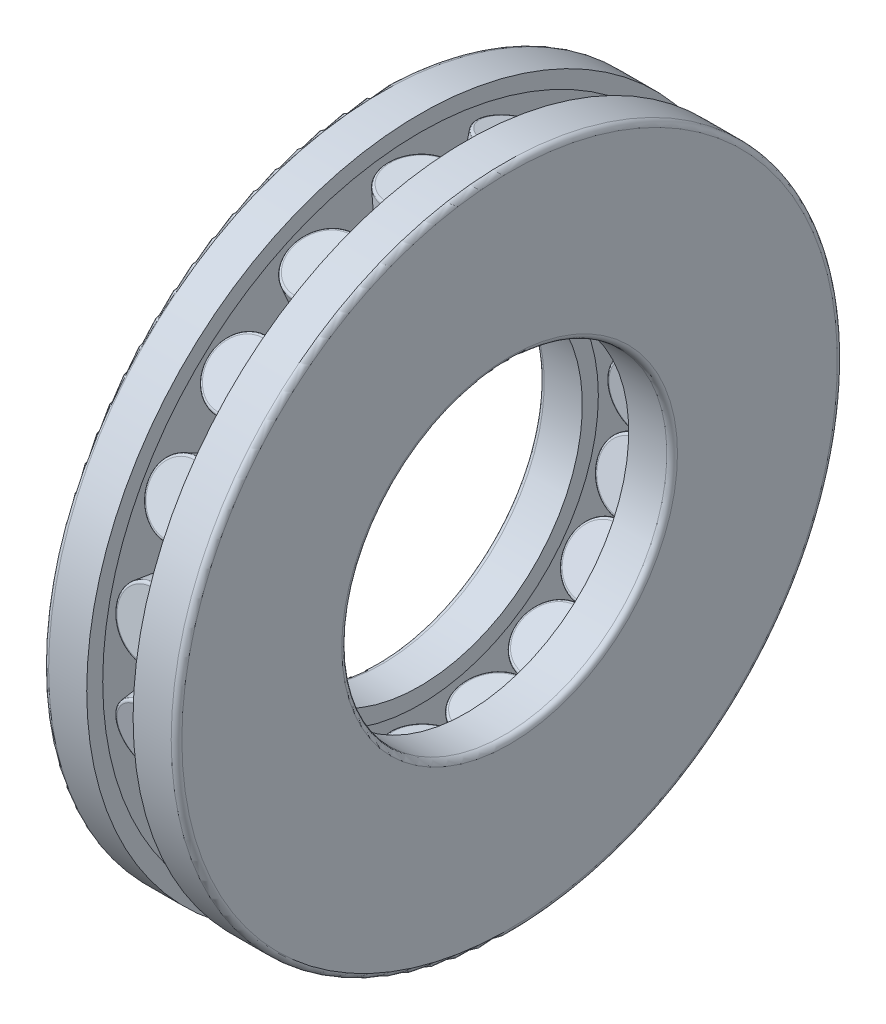
SolidWorks part; units mm, degrees
ref_plane "Front Plane" through (0, 0, 0) normal (0, 0, 1) x (1, 0, 0)
ref_plane "Top Plane" through (0, 0, 0) normal (0, 1, 0) x (1, 0, 0)
ref_plane "Right Plane" through (0, 0, 0) normal (1, 0, 0) x (0, 0, -1)
sketch "Sketch1" plane through (0, 0, 0) normal (0, 1, 0) x (1, 0, 0)
  line L0 (6.35, 62.5) -> (4.35, 62.5)
  line L1 (6.35, 30.5) -> (11.5, 30.5)
  line L2 (6.35, 30.5) -> (6.35, 62.5) construction
  line L3 (6.35, 62.5) -> (11.5, 62.5)
  line L4 (12.5, 31.5) -> (12.5, 61.5)
  line L5 (4.35, 62.5) -> (4.35, 59.5)
  line L6 (4.35, 59.5) -> (6.35, 59.5)
  line L7 (6.35, 46.5) -> (12.5, 46.5) construction
  line L8 (4.35, 33.5) -> (6.35, 33.5)
  line L9 (4.35, 30.5) -> (4.35, 33.5)
  line L10 (6.35, 30.5) -> (4.35, 30.5)
  line L11 (6.35, 59.5) -> (6.35, 33.5)
  line L12 (0, -55) -> (0, 55) construction
  line L13 (-6.35, 46.5) -> (-12.5, 46.5) construction
  line L14 (-6.35, 30.5) -> (-6.35, 62.5) construction
  line L15 (-6.35, 59.5) -> (-6.35, 33.5)
  line L16 (-6.35, 30.5) -> (-4.35, 30.5)
  line L17 (-4.35, 30.5) -> (-4.35, 33.5)
  line L18 (-4.35, 33.5) -> (-6.35, 33.5)
  line L19 (-4.35, 59.5) -> (-6.35, 59.5)
  line L20 (-4.35, 62.5) -> (-4.35, 59.5)
  line L21 (-12.5, 31.5) -> (-12.5, 61.5)
  line L22 (-6.35, 62.5) -> (-11.5, 62.5)
  line L23 (-6.35, 30.5) -> (-11.5, 30.5)
  line L24 (-6.35, 62.5) -> (-4.35, 62.5)
  line L25 (0, 0) -> (5.15, 0) construction
  arc A0 (11.5, 30.5) -> (12.5, 31.5) centre (11.5, 31.5) ccw
  arc A1 (11.5, 62.5) -> (12.5, 61.5) centre (11.5, 61.5) cw
  arc A2 (-11.5, 62.5) -> (-12.5, 61.5) centre (-11.5, 61.5) ccw
  arc A3 (-11.5, 30.5) -> (-12.5, 31.5) centre (-11.5, 31.5) cw
  point P10 (12.5, 30.5)
  point P13 (12.5, 62.5)
  point P38 (-12.5, 62.5)
  point P39 (-12.5, 30.5)
  dimension "D5" = 1
  dimension "D1" = 32
  dimension "D2" = 6.15
  dimension "D3" = 30.5
  dimension "D4" = 6.35
  dimension "D6" = 2
  dimension "D7" = 3
revolve "Revolve1" add sketch "Sketch1" angle 360 about L25
sketch "Sketch3" plane through (0, 0, 0) normal (0, 1, 0) x (1, 0, 0)
  line L1 (0, 36.875) -> (5.75, 36.875)
  line L2 (0, 36.875) -> (0, 56.125)
  line L3 (0, 56.125) -> (5.75, 56.125)
  line L4 (6.25, 37.375) -> (6.25, 55.625)
  arc A0 (5.75, 36.875) -> (6.25, 37.375) centre (5.75, 37.375) ccw
  arc A1 (5.75, 56.125) -> (6.25, 55.625) centre (5.75, 55.625) cw
  point P6 (0, 46.5)
  point P10 (6.25, 36.875)
  point P13 (6.25, 56.125)
  dimension "D3" = 0.5
  dimension "D1" = 6.25
  dimension "D2" = 19.25
revolve "Revolve2" add sketch "Sketch3" angle 360 about L2
pattern_circular "CirPattern1" count 19 over 360 about axis through (0, 0, 0) along (1, 0, 0) of bodies 103
